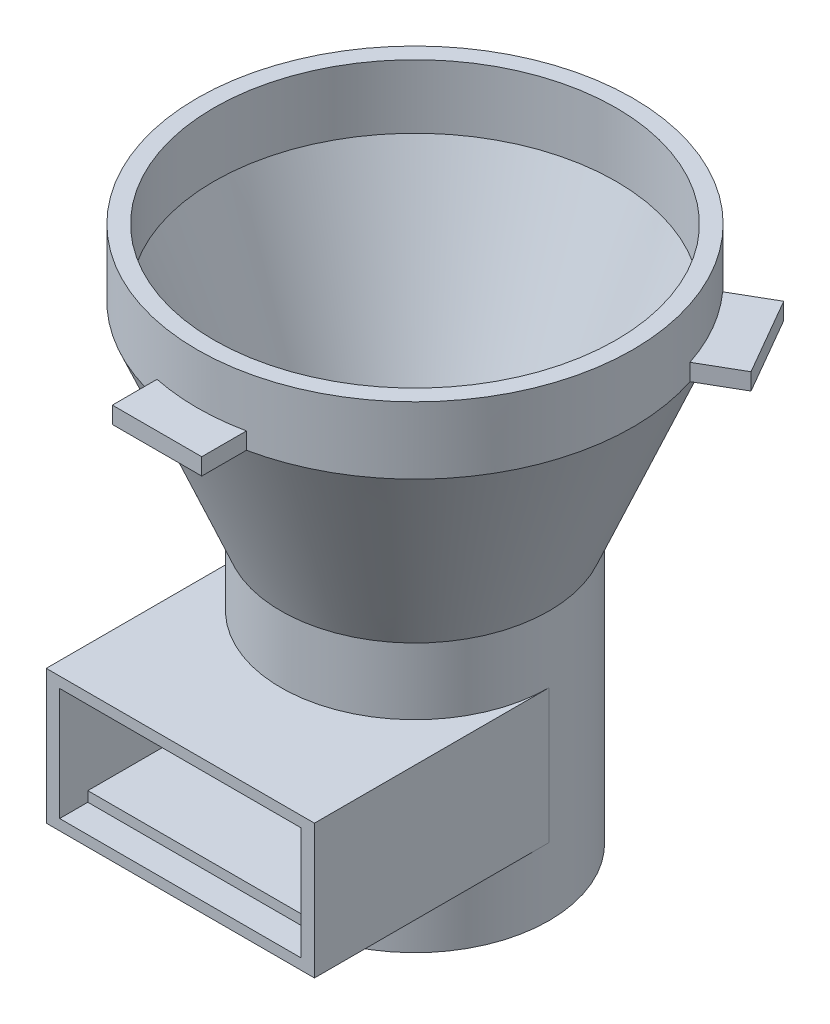
SolidWorks part; units mm, degrees
ref_plane "Front Plane" through (0, 0, 0) normal (0, 0, 1) x (1, 0, 0)
ref_plane "Top Plane" through (0, 0, 0) normal (0, 1, 0) x (1, 0, 0)
ref_plane "Right Plane" through (0, 0, 0) normal (1, 0, 0) x (0, 0, -1)
sketch "Sketch1" plane through (0, 0, 0) normal (0, 0, 1) x (1, 0, 0)
  line L0 (0, 0) -> (0, 92.075) construction
  line L1 (0, 92.075) -> (-41.275, 92.075)
  line L2 (-41.275, 92.075) -> (-41.275, 88.9)
  line L3 (-41.275, 88.9) -> (-25.4, 50.8)
  line L4 (-25.4, 50.8) -> (-25.4, 0)
  line L5 (-25.4, 0) -> (0, 0)
  line L6 (0, 0) -> (0, 92.075)
  dimension "D1" = 3.175
  dimension "D2" = 38.1
  dimension "D3" = 41.275
  dimension "D4" = 50.8
  dimension "D5" = 25.4
revolve "Revolve1" add sketch "Sketch1" angle 360 about L0
shell "Shell1" thickness 3.175
sketch "Sketch2" plane through (0, 92.075, 0) normal (0, 1, 0) x (1, 0, 0)
  line L1 (0, -48.864) -> (-8.4667, -48.864)
  line L2 (-8.4667, -48.864) -> (-8.4667, -40.3973)
  line L3 (0, -48.864) -> (8.4667, -48.864)
  line L4 (8.4667, -48.864) -> (8.4667, -40.3973)
  circle A0 centre (0, 0) radius 41.275 construction
  arc A1 (-8.4667, -40.3973) -> (8.4667, -40.3973) centre (0, 0) ccw
  dimension "D1" = 16.9333
  dimension "D2" = 8.4667
extrude "Boss-Extrude1" add sketch "Sketch2" against normal blind 3.175
pattern_circular "CirPattern1" count 3 every 120 about axis through (0, 0, 0) along (0, 1, 0) of "Boss-Extrude1"
sketch "Sketch4" plane through (0, 0, 0) normal (0, 0, 1) x (1, 0, 0)
  line L0 (-25.4, 50.8) -> (-25.4, 0) construction
  line L1 (-25.4, 38.2205) -> (25.4, 38.2205)
  line L2 (-25.4, 38.2205) -> (-25.4, 12.8205)
  line L3 (-25.4, 12.8205) -> (25.4, 12.8205)
  line L4 (25.4, 38.2205) -> (25.4, 12.8205)
  line L5 (25.4, 0) -> (25.4, 50.8) construction
  dimension "D1" = 25.4
extrude "Boss-Extrude2" add sketch "Sketch4" along normal blind 44.45
sketch "Sketch5" plane through (0, 38.2205, 0) normal (0, 1, 0) x (1, 0, 0)
  circle A0 centre (0, 0) radius 22.225
extrude "Cut-Extrude1" cut sketch "Sketch5" against normal through all both and the other way through all
sketch "Sketch6" plane through (0, 0, 44.45) normal (0, 0, 1) x (1, 0, 0)
  line L0 (0, 12.8205) -> (0, 38.2205) construction
  line L1 (-25.4, 12.8205) -> (25.4, 12.8205) construction
  line L2 (25.4, 38.2205) -> (-25.4, 38.2205) construction
  line L4 (-22.86, 14.8525) -> (22.86, 14.8525)
  line L5 (-22.86, 14.8525) -> (-22.86, 36.1885)
  line L6 (-22.86, 36.1885) -> (22.86, 36.1885)
  line L7 (22.86, 14.8525) -> (22.86, 36.1885)
  line L8 (-22.86, 14.8525) -> (22.86, 36.1885) construction
  line L9 (-22.86, 36.1885) -> (22.86, 14.8525) construction
  point P6 (0, 25.5205)
  dimension "D1" = 21.336
  dimension "D2" = 45.72
extrude "Cut-Extrude2" cut sketch "Sketch6" against normal blind 40.767
sketch "Sketch7" plane through (0, 14.8525, 0) normal (0, 1, 0) x (1, 0, 0)
  line L0 (0, -22.8604) -> (-22.86, -22.8604)
  line L2 (-22.86, -3.683) -> (-22.86, -44.45) construction
  line L3 (-22.86, -22.8604) -> (-22.8604, 0)
  line L4 (0, -22.8604) -> (22.86, -22.8604)
  line L5 (22.86, -3.683) -> (22.86, -44.45) construction
  line L6 (22.86, -22.8604) -> (22.8604, 0)
  line L7 (-22.8604, 0) -> (-22.225, 0)
  line L8 (21.9177, -3.683) -> (22.86, -3.683)
  line L9 (22.86, -3.683) -> (22.8604, 0)
  arc A2 (-22.225, 0) -> (21.9177, -3.683) centre (0, 0) ccw
  arc A3 (-21.9177, -3.683) -> (21.9177, -3.683) centre (0, 0) ccw construction
extrude "Boss-Extrude3" add sketch "Sketch7" along normal blind 1.905
sketch "Sketch8" plane through (0, 0, 22.8604) normal (0, 0, 1) x (1, 0, 0)
  line L1 (-22.86, 16.7575) -> (22.86, 16.7575)
  line L2 (-22.86, 16.7575) -> (-22.86, 14.8525)
  line L3 (-22.86, 14.8525) -> (22.86, 14.8525)
  line L4 (22.86, 16.7575) -> (22.86, 14.8525)
extrude "Boss-Extrude4" add sketch "Sketch8" along normal blind 16.256
sketch "Sketch10" plane through (0, 92.075, 0) normal (0, 1, 0) x (1, 0, 0)
  circle A0 centre (0, 0) radius 38.1
  circle A1 centre (0, 0) radius 41.275
extrude "Boss-Extrude5" add sketch "Sketch10" along normal blind 9.525
